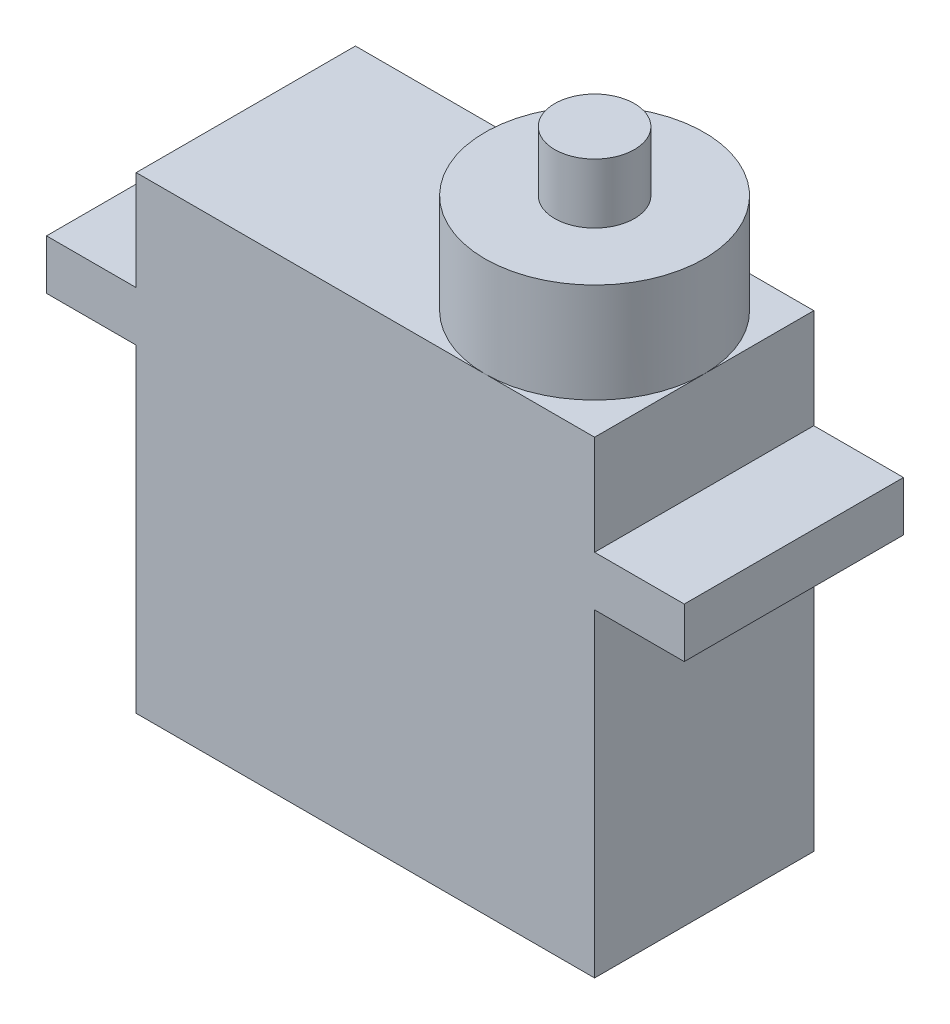
SolidWorks part; units mm, degrees
ref_plane "Front Plane" through (0, 0, 0) normal (0, 0, 1) x (1, 0, 0)
ref_plane "Top Plane" through (0, 0, 0) normal (0, 1, 0) x (1, 0, 0)
ref_plane "Right Plane" through (0, 0, 0) normal (1, 0, 0) x (0, 0, -1)
sketch "Sketch1" plane through (0, 0, 0) normal (0, 1, 0) x (1, 0, 0)
  line L1 (-11.5, 5.5) -> (11.5, 5.5)
  line L2 (-11.5, 5.5) -> (-11.5, -5.5)
  line L3 (-11.5, -5.5) -> (11.5, -5.5)
  line L4 (11.5, 5.5) -> (11.5, -5.5)
  line L5 (-11.5, 5.5) -> (11.5, -5.5) construction
  line L6 (-11.5, -5.5) -> (11.5, 5.5) construction
  point P0 (0, 0)
  dimension "D1" = 23
  dimension "D2" = 11
extrude "Boss-Extrude1" add sketch "Sketch1" along normal blind 16
sketch "Sketch2" plane through (0, 16, 0) normal (0, 1, 0) x (1, 0, 0)
  line L1 (-16, 5.5) -> (16, 5.5)
  line L2 (-16, 5.5) -> (-16, -5.5)
  line L3 (-16, -5.5) -> (16, -5.5)
  line L4 (16, 5.5) -> (16, -5.5)
  line L5 (-16, 5.5) -> (16, -5.5) construction
  line L6 (-16, -5.5) -> (16, 5.5) construction
  point P0 (0, 0)
  dimension "D1" = 11
  dimension "D2" = 32
extrude "Boss-Extrude2" add sketch "Sketch2" along normal blind 2.5
sketch "Sketch3" plane through (0, 18.5, 0) normal (0, 1, 0) x (1, 0, 0)
  line L0 (-16, -5.5) -> (16, -5.5) construction
  line L1 (-11.5, 5.5) -> (11.5, 5.5)
  line L2 (-11.5, 5.5) -> (-11.5, -5.5)
  line L3 (-11.5, -5.5) -> (11.5, -5.5)
  line L4 (11.5, 5.5) -> (11.5, -5.5)
  line L5 (-11.5, 5.5) -> (11.5, -5.5) construction
  line L6 (-11.5, -5.5) -> (11.5, 5.5) construction
  point P0 (0, 0)
  dimension "D1" = 23
extrude "Boss-Extrude3" add sketch "Sketch3" along normal blind 5
sketch "Sketch4" plane through (0, 23.5, 0) normal (0, 1, 0) x (1, 0, 0)
  line L1 (11.5, -5.5) -> (6, -5.5)
  line L2 (11.5, -5.5) -> (11.5, 0)
  line L3 (11.5, 0) -> (6, 0)
  line L4 (6, -5.5) -> (6, 0)
  circle A0 centre (6, 0) radius 5.5
  dimension "D1" = 5.5
extrude "Boss-Extrude4" add sketch "Sketch4" along normal blind 5 contours L3 A0 L4 | L4 A0 L3
sketch "Sketch5" plane through (0, 28.5, 0) normal (0, 1, 0) x (1, 0, 0)
  line L1 (11.5, -5.5) -> (6, -5.5)
  line L2 (11.5, -5.5) -> (11.5, 0)
  line L3 (11.5, 0) -> (6, 0)
  line L4 (6, -5.5) -> (6, 0)
  circle A0 centre (6, 0) radius 2
  dimension "D2" = 4
  dimension "D1" = 5.5
extrude "Boss-Extrude5" add sketch "Sketch5" along normal blind 3 contours L3 A0 L4 | L4 A0 L3
